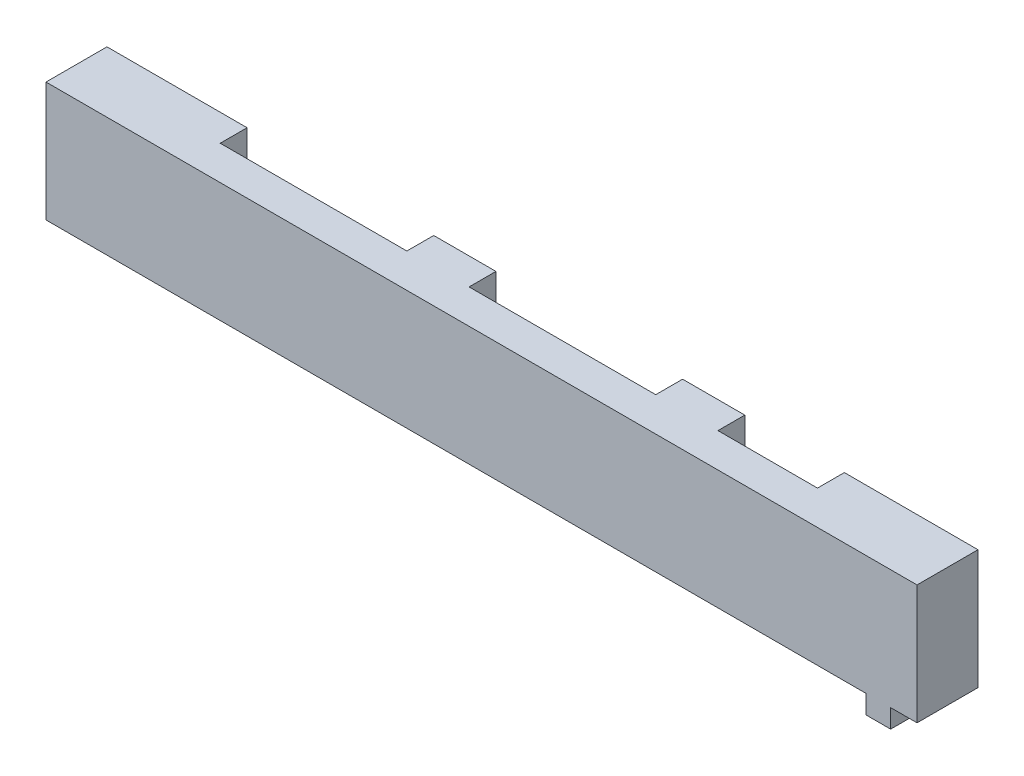
SolidWorks part; units mm, degrees
ref_plane "前视基准面" through (0, 0, 0) normal (0, 0, 1) x (1, 0, 0)
ref_plane "上视基准面" through (0, 0, 0) normal (0, 1, 0) x (1, 0, 0)
ref_plane "右视基准面" through (0, 0, 0) normal (1, 0, 0) x (0, 0, -1)
other "Configuration Table"
sketch "草图1" plane through (0, 0, 0) normal (1, 0, 0) x (0, 0, -1)
  line L1 (-1.9234, 1.2494) -> (2.9766, 1.2494)
  line L2 (-1.9234, 1.2494) -> (-1.9234, -8.3506)
  line L3 (-1.9234, -8.3506) -> (2.9766, -8.3506)
  line L4 (2.9766, 1.2494) -> (2.9766, -8.3506)
  line L5 (-1.9234, 1.2494) -> (2.9766, -8.3506) construction
  line L6 (-1.9234, -8.3506) -> (2.9766, 1.2494) construction
  point P0 (0.5266, -3.5506)
  dimension "D1" = 4.9
  dimension "D2" = 9.6
extrude "凸台-拉伸1" add sketch "草图1" along normal blind 70
sketch "草图2" plane through (0, -8.3506, 0) normal (0, -1, 0) x (1, 0, 0)
  line L0 (70, -2.9766) -> (0, -2.9766) construction
  line L2 (51.26, -2.9766) -> (51.26, -0.8173)
  line L4 (46.26, -2.9766) -> (46.26, -0.8173)
  line L5 (70, 1.9234) -> (70, -2.9766) construction
  line L6 (31.26, -2.9766) -> (31.26, -0.8173)
  line L8 (26.26, -2.9766) -> (26.26, -0.8173)
  line L10 (11.26, -2.9766) -> (11.26, -0.8173)
  line L17 (59.26, -2.9766) -> (51.26, -2.9766)
  line L19 (51.26, -0.8173) -> (59.26, -0.8173)
  line L20 (31.26, -0.8173) -> (46.26, -0.8173)
  line L21 (11.26, -0.8173) -> (26.26, -0.8173)
  line L24 (26.26, -2.9766) -> (11.26, -2.9766)
  line L26 (46.26, -2.9766) -> (31.26, -2.9766)
  line L27 (59.26, -0.8173) -> (59.26, -2.9766)
  line L29 (6.26, -2.9766) -> (6.26, -0.8173) [skipped]
  dimension "D1" = 18.74
  dimension "D2" = 5
  dimension "D3" = 3
  dimension "D4" = 8
extrude "切除-拉伸1" cut sketch "草图2" against normal through all
sketch "草图3" plane through (0, -8.3506, 0) normal (0, -1, 0) x (1, 0, 0)
  line L0 (70, 1.9234) -> (0, 1.9234) construction
  line L1 (67.88, 1.9234) -> (65.88, 1.9234)
  line L2 (67.88, 1.9234) -> (67.88, -2.9766)
  line L3 (67.88, -2.9766) -> (65.88, -2.9766)
  line L4 (65.88, 1.9234) -> (65.88, -2.9766)
  line L5 (70, -2.9766) -> (59.26, -2.9766) construction
  line L6 (70, 1.9234) -> (70, -2.9766) construction
  dimension "D1" = 2.12
  dimension "D2" = 2
extrude "凸台-拉伸2" add sketch "草图3" along normal blind 1.5
